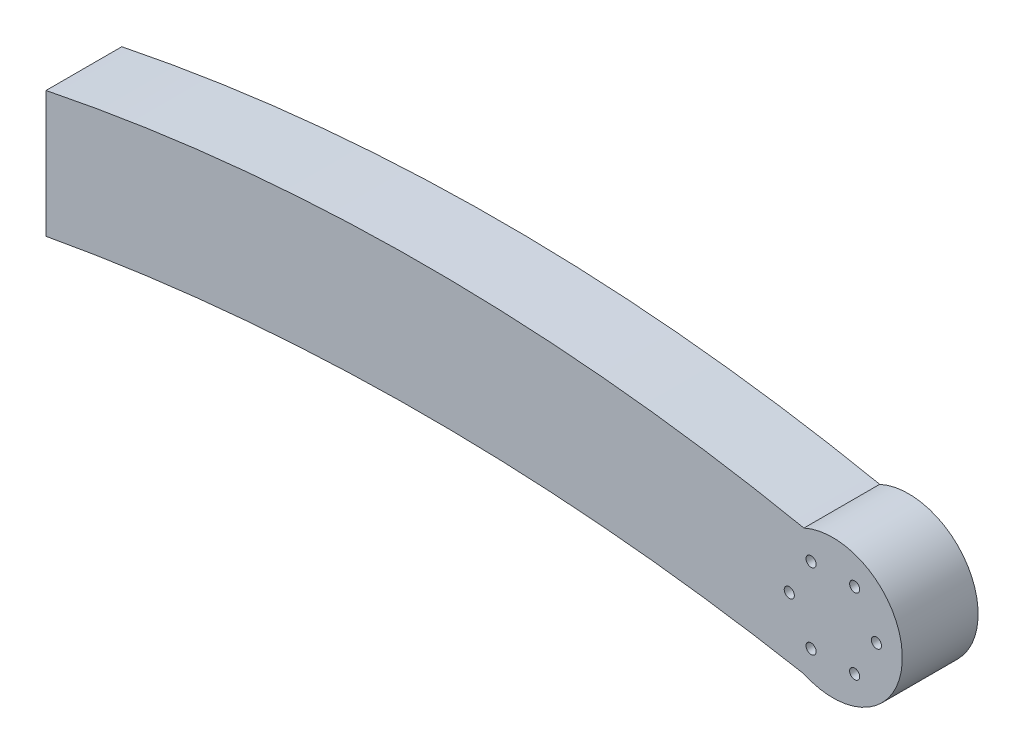
SolidWorks part; units mm, degrees
ref_plane "前视基准面" through (0, 0, 0) normal (0, 0, 1) x (1, 0, 0)
ref_plane "上视基准面" through (0, 0, 0) normal (0, 1, 0) x (1, 0, 0)
ref_plane "右视基准面" through (0, 0, 0) normal (1, 0, 0) x (0, 0, -1)
sketch "草图1" plane through (0, 0, 0) normal (0, 0, 1) x (1, 0, 0)
  line L1 (-150, 25) -> (150, 25)
  line L2 (-150, 25) -> (-150, -25)
  line L3 (-150, -25) -> (150, -25)
  line L4 (150, 25) -> (150, -25)
  line L5 (-150, 25) -> (150, -25) construction
  line L6 (-150, -25) -> (150, 25) construction
  arc A0 (-150, 25) -> (150, 25) centre (0, -709.8469) cw
  arc A1 (-150, -25) -> (150, -25) centre (0, -836.1946) cw
  circle A2 centre (161.4564, 0) radius 27.5
  point P0 (0, 0)
  dimension "D3" = 750
  dimension "D4" = 824.9465
  dimension "D5" = 55
  dimension "D1" = 300
  dimension "D2" = 50
extrude "凸台-拉伸1" add sketch "草图1" along normal blind 30 contours A2 L1 L2 A1 | A0 L1 | L4 A2
sketch "草图2" plane through (0, 0, 30) normal (0, 0, 1) x (1, 0, 0)
  line L1 (-150, 25) -> (-150, -25)
  line L2 (-150, 25) -> (-150, -25)
  circle A0 centre (161.4564, 0) radius 17.25 construction
  circle A1 centre (178.7064, 0) radius 2
  circle A2 centre (170.0814, -14.9389) radius 2
  arc A3 (150, -25) -> (-150, -25) centre (0, -836.1946) ccw
  arc A4 (150, -25) -> (150, 25) centre (161.4564, 0) ccw
  arc A5 (150, 25) -> (-150, 25) centre (0, -709.8469) ccw
  arc A6 (150, -25) -> (-150, -25) centre (0, -836.1946) ccw
  arc A7 (150, -25) -> (150, 25) centre (161.4564, 0) ccw
  arc A8 (150, 25) -> (-150, 25) centre (0, -709.8469) ccw
  circle A9 centre (152.8314, -14.9389) radius 2
  circle A10 centre (144.2064, 0) radius 2
  circle A11 centre (152.8314, 14.9389) radius 2
  circle A12 centre (170.0814, 14.9389) radius 2
  point P22 (161.4564, 0)
  dimension "D2" = 34.5
  dimension "D3" = 4
  dimension "D1" = 0
  dimension "D4" = 6
extrude "切除-拉伸1" cut sketch "草图2" against normal through all contours A11 | A10 | A9 | A2 | A1 | A12
